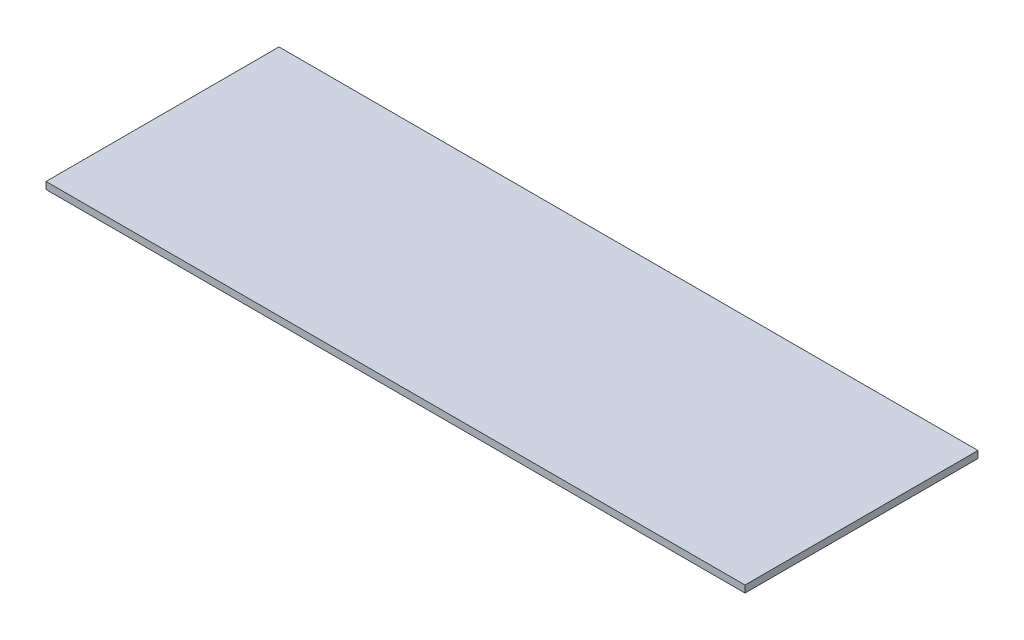
SolidWorks part; units mm, degrees
ref_plane "Front Plane" through (0, 0, 0) normal (0, 0, 1) x (1, 0, 0)
ref_plane "Top Plane" through (0, 0, 0) normal (0, 1, 0) x (1, 0, 0)
ref_plane "Right Plane" through (0, 0, 0) normal (1, 0, 0) x (0, 0, -1)
sketch "Sketch1" plane through (0, 0, 0) normal (0, 1, 0) x (1, 0, 0)
  line L1 (-9.9432, -81.5057) -> (290.0568, -81.5057)
  line L2 (-9.9432, -81.5057) -> (-9.9432, 18.4943)
  line L3 (-9.9432, 18.4943) -> (290.0568, 18.4943)
  line L4 (290.0568, -81.5057) -> (290.0568, 18.4943)
  dimension "D1" = 300
  dimension "D2" = 100
extrude "Boss-Extrude1" add sketch "Sketch1" along normal blind 3
